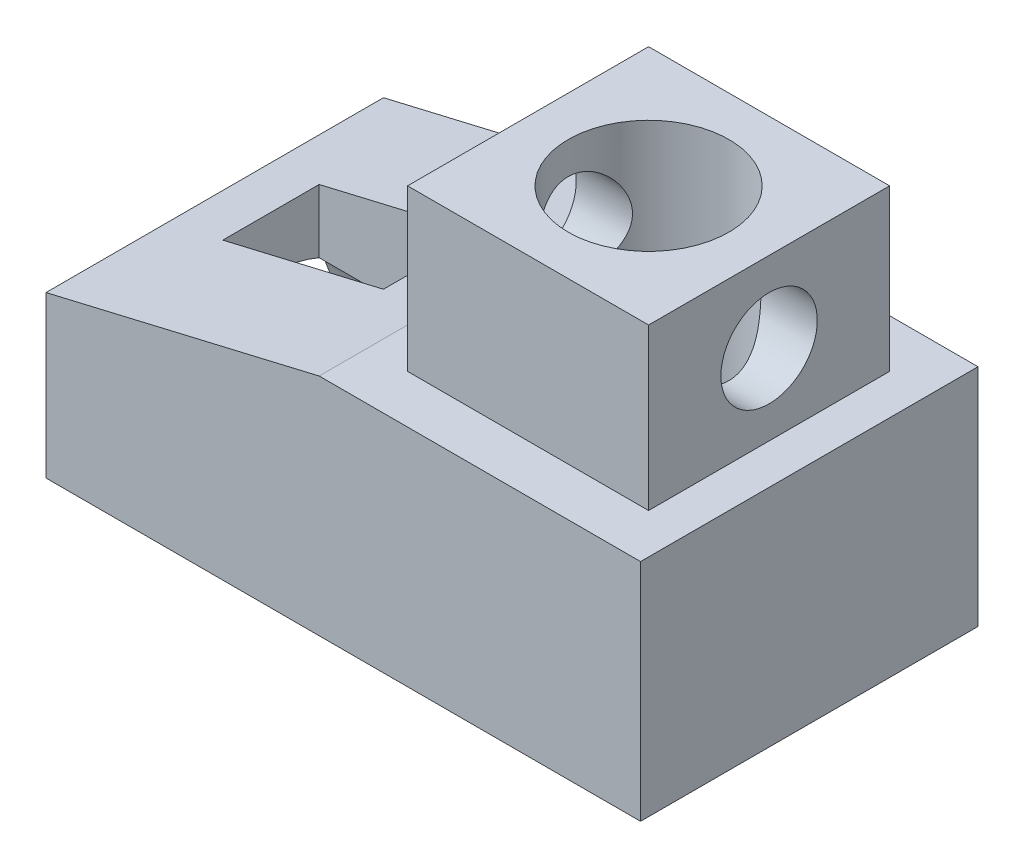
SolidWorks part; units mm, degrees
ref_plane "Front Plane" through (0, 0, 0) normal (0, 0, 1) x (1, 0, 0)
ref_plane "Top Plane" through (0, 0, 0) normal (0, 1, 0) x (1, 0, 0)
ref_plane "Right Plane" through (0, 0, 0) normal (1, 0, 0) x (0, 0, -1)
sketch "Sketch2" plane through (0, 0, 0) normal (0, 0, 1) x (1, 0, 0)
  line L0 (0, 28) -> (39, 28)
  line L1 (0, 0) -> (74, 0)
  line L2 (0, 0) -> (0, 28)
  line L3 (39, 48) -> (69, 48)
  line L4 (74, 0) -> (74, 28)
  line L5 (69, 48) -> (69, 28)
  line L6 (39, 48) -> (39, 28)
  line L7 (69, 28) -> (74, 28)
  dimension "D1" = 74
  dimension "D2" = 20
  dimension "D3" = 28
  dimension "D4" = 5
  dimension "D5" = 30
extrude "Boss-Extrude1" add sketch "Sketch2" along normal blind 42
sketch "Sketch3" plane through (0, 28, 0) normal (0, 1, 0) x (1, 0, 0)
  line L1 (7, -15) -> (27, -15)
  line L2 (7, -15) -> (7, -27)
  line L3 (7, -27) -> (27, -27)
  line L4 (39, 0) -> (0, 0)
  line L5 (0, 0) -> (0, -42)
  line L6 (0, -42) -> (39, -42)
  line L7 (39, -42) -> (39, 0)
  line L8 (39, 0) -> (0, 0)
  line L9 (0, 0) -> (0, -42)
  line L10 (0, -42) -> (39, -42)
  line L11 (39, -42) -> (39, 0)
  line L12 (27, -15) -> (27, -27)
  dimension "D2" = 7
  dimension "D3" = 20
  dimension "D4" = 12
  dimension "D5" = 15
  dimension "D1" = 0
extrude "Cut-Extrude1" cut sketch "Sketch3" against normal blind 42 contours L2 L1 L12 L3
sketch "Sketch4" plane through (0, 0, 42) normal (0, 0, 1) x (1, 0, 0)
  line L0 (34, 28) -> (0, 20)
  line L8 (0, 28) -> (0, 0)
  line L9 (0, 0) -> (74, 0)
  line L10 (74, 0) -> (74, 28)
  line L11 (74, 28) -> (69, 28)
  line L12 (69, 28) -> (69, 48)
  line L13 (69, 48) -> (39, 48)
  line L14 (39, 48) -> (39, 28)
  line L15 (39, 28) -> (0, 28)
  line L16 (0, 28) -> (0, 0)
  line L17 (0, 0) -> (74, 0)
  line L18 (74, 0) -> (74, 28)
  line L19 (74, 28) -> (69, 28)
  line L20 (69, 28) -> (69, 48)
  line L21 (69, 48) -> (39, 48)
  line L22 (39, 48) -> (39, 28)
  line L23 (39, 28) -> (0, 28)
  line M9 (0, 28) -> (0, 0)
  line M16 (39, 28) -> (0, 28)
  dimension "D2" = 5
  dimension "D3" = 20
  dimension "D1" = 0
extrude "Cut-Extrude2" cut sketch "Sketch4" against normal blind 45 contours L0 M16 M9
sketch "Sketch5" plane through (0, 0, 42) normal (0, 0, 1) x (1, 0, 0)
  line L0 (39, 28) -> (69, 28)
  line L9 (34, 28) -> (0, 20)
  line L10 (0, 20) -> (0, 0)
  line L11 (0, 0) -> (74, 0)
  line L12 (74, 0) -> (74, 28)
  line L13 (74, 28) -> (69, 28)
  line L14 (69, 28) -> (69, 48)
  line L15 (69, 48) -> (39, 48)
  line L16 (39, 48) -> (39, 28)
  line L17 (39, 28) -> (34, 28)
  line L18 (34, 28) -> (0, 20)
  line L19 (0, 20) -> (0, 0)
  line L20 (0, 0) -> (74, 0)
  line L21 (74, 0) -> (74, 28)
  line L22 (74, 28) -> (69, 28)
  line L23 (69, 28) -> (69, 48)
  line L24 (69, 48) -> (39, 48)
  line L25 (39, 48) -> (39, 28)
  line L26 (39, 28) -> (34, 28)
  line M15 (69, 28) -> (69, 48)
  line M16 (69, 48) -> (39, 48)
  line M17 (39, 48) -> (39, 28)
  dimension "D1" = 0
extrude "Cut-Extrude3" cut sketch "Sketch5" against normal blind 6 contours L0 M17 M15 M16
sketch "Sketch6" plane through (0, 0, 0) normal (0, 0, -1) x (-1, 0, 0)
  line L0 (-69, 28) -> (-39, 28)
  line L9 (0, 0) -> (0, 20)
  line L10 (0, 20) -> (-34, 28)
  line L11 (-34, 28) -> (-39, 28)
  line L12 (-39, 28) -> (-39, 48)
  line L13 (-39, 48) -> (-69, 48)
  line L14 (-69, 48) -> (-69, 28)
  line L15 (-69, 28) -> (-74, 28)
  line L16 (-74, 28) -> (-74, 0)
  line L17 (-74, 0) -> (0, 0)
  line L18 (0, 0) -> (0, 20)
  line L19 (0, 20) -> (-34, 28)
  line L20 (-34, 28) -> (-39, 28)
  line L21 (-39, 28) -> (-39, 48)
  line L22 (-39, 48) -> (-69, 48)
  line L23 (-69, 48) -> (-69, 28)
  line L24 (-69, 28) -> (-74, 28)
  line L25 (-74, 28) -> (-74, 0)
  line L26 (-74, 0) -> (0, 0)
  line M13 (-39, 28) -> (-39, 48)
  line M14 (-39, 48) -> (-69, 48)
  line M15 (-69, 48) -> (-69, 28)
  dimension "D1" = 0
extrude "Cut-Extrude4" cut sketch "Sketch6" against normal blind 6 contours L0 M15 M13 M14
sketch "Sketch7" plane through (0, 0, 0) normal (-1, 0, 0) x (0, 0, 1)
  line L4 (42, 20) -> (0, 20)
  line L5 (0, 20) -> (0, 0)
  line L6 (0, 0) -> (42, 0)
  line L7 (42, 0) -> (42, 20)
  line L8 (42, 20) -> (0, 20)
  line L9 (0, 20) -> (0, 0)
  line L10 (0, 0) -> (42, 0)
  line L11 (42, 0) -> (42, 20)
  circle A0 centre (21, 0) radius 7.5
  dimension "D2" = 15
  dimension "D1" = 0
extrude "Cut-Extrude5" cut sketch "Sketch7" against normal blind 27 contours L10 A0
sketch "Sketch8" plane through (39, 0, 0) normal (-1, 0, 0) x (0, 0, 1)
  line L4 (6, 48) -> (6, 28)
  line L5 (6, 28) -> (36, 28)
  line L6 (36, 28) -> (36, 48)
  line L7 (36, 48) -> (6, 48)
  line L8 (6, 48) -> (6, 28)
  line L9 (6, 28) -> (36, 28)
  line L10 (36, 28) -> (36, 48)
  line L11 (36, 48) -> (6, 48)
  circle A0 centre (21, 38) radius 6
  dimension "D2" = 12
  dimension "D3" = 10
  dimension "D4" = 15
  dimension "D1" = 0
extrude "Cut-Extrude6" cut sketch "Sketch8" against normal blind 42 contours A0
sketch "Sketch9" plane through (0, 48, 0) normal (0, 1, 0) x (1, 0, 0)
  line L4 (69, -6) -> (39, -6)
  line L5 (39, -6) -> (39, -36)
  line L6 (39, -36) -> (69, -36)
  line L7 (69, -36) -> (69, -6)
  line L8 (69, -6) -> (39, -6)
  line L9 (39, -6) -> (39, -36)
  line L10 (39, -36) -> (69, -36)
  line L11 (69, -36) -> (69, -6)
  circle A0 centre (54, -21) radius 7.5
  dimension "D2" = 15
  dimension "D3" = 15
  dimension "D4" = 15
  dimension "D1" = 0
extrude "Cut-Extrude7" cut sketch "Sketch9" against normal blind 70 contours A0
sketch "Sketch10" plane through (0, 0, 0) normal (-1, 0, 0) x (0, 0, 1)
  line L5 (0, 0) -> (13.5, 0)
  line L6 (28.5, 0) -> (42, 0)
  line L7 (42, 0) -> (42, 20)
  line L8 (42, 20) -> (0, 20)
  line L9 (0, 20) -> (0, 0)
  line L10 (0, 0) -> (13.5, 0)
  line L11 (28.5, 0) -> (42, 0)
  line L12 (42, 0) -> (42, 20)
  line L13 (42, 20) -> (0, 20)
  line L14 (0, 20) -> (0, 0)
  circle A0 centre (21, 0) radius 15
  arc A1 (28.5, 0) -> (13.5, 0) centre (21, 0) ccw
  arc A2 (28.5, 0) -> (13.5, 0) centre (21, 0) ccw
  arc M8 (13.5, 0) -> (28.5, 0) centre (21, 0) cw
  line M9 (28.5, 0) -> (42, 0)
  dimension "D2" = 30
  dimension "D1" = 0
extrude "Cut-Extrude8" cut sketch "Sketch10" against normal blind 27 contours A0 L10 M9 M8
sketch "Sketch11" plane through (0, 48, 0) normal (0, 1, 0) x (1, 0, 0)
  line L4 (69, -6) -> (39, -6)
  line L5 (39, -6) -> (39, -36)
  line L6 (39, -36) -> (69, -36)
  line L7 (69, -36) -> (69, -6)
  line L8 (69, -6) -> (39, -6)
  line L9 (39, -6) -> (39, -36)
  line L10 (39, -36) -> (69, -36)
  line L11 (69, -36) -> (69, -6)
  circle A0 centre (54, -21) radius 10
  dimension "D2" = 20
  dimension "D1" = 0
extrude "Cut-Extrude9" cut sketch "Sketch11" against normal blind 58 contours A0
